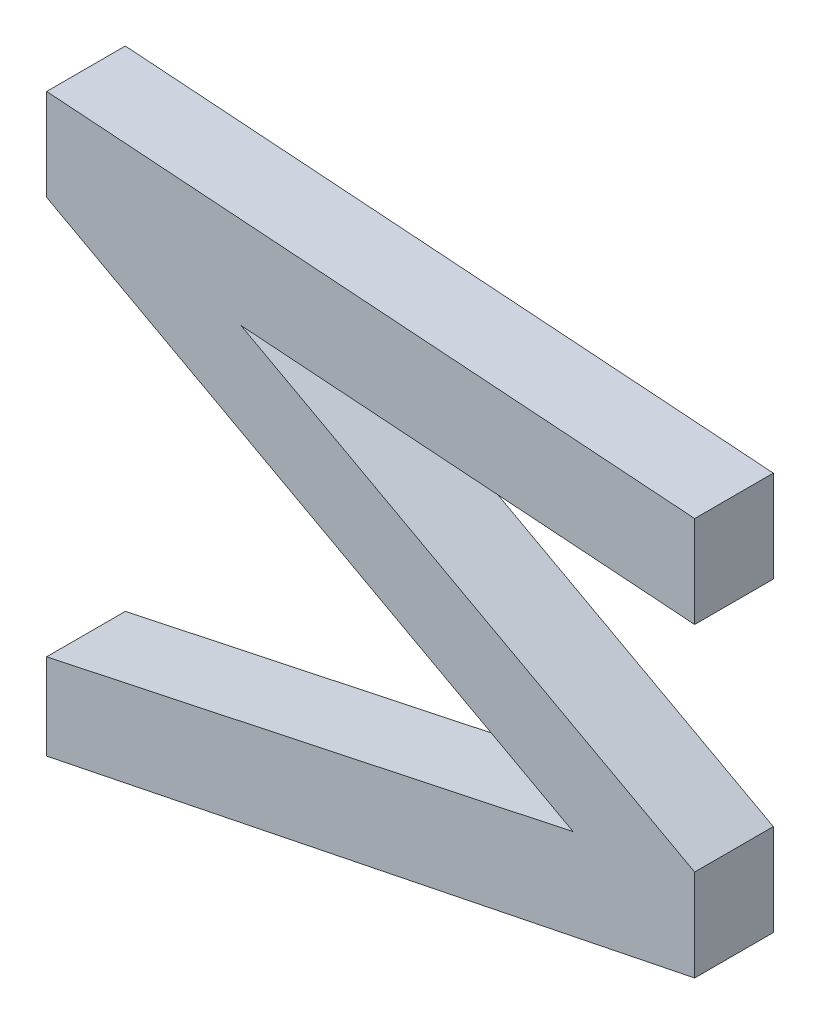
SolidWorks part; units mm, degrees
material "ABS"
ref_plane "Front Plane" through (0, 0, 0) normal (0, 0, 1) x (1, 0, 0)
ref_plane "Top Plane" through (0, 0, 0) normal (0, 1, 0) x (1, 0, 0)
ref_plane "Right Plane" through (0, 0, 0) normal (1, 0, 0) x (0, 0, -1)
sketch "Sketch1" plane through (0, 0, 74.3091) normal (0, 0, 1) x (1, 0, 0)
  line L0 (-16.8386, 48.4772) -> (-79.602, 52.9222)
  line L1 (-79.602, 52.9222) -> (-79.602, 44.0322)
  line L2 (-79.602, 37.7408) -> (-79.602, 52.9222) construction
  line L3 (-16.8386, 48.4772) -> (-16.8386, 39.5872)
  line L4 (-16.8386, 48.4772) -> (-16.8386, 9.9372) construction
  line L5 (-28.6045, 40.4205) -> (-60.7836, 42.6995)
  line L6 (-16.8386, 9.9372) -> (-79.602, -2.8314)
  line L7 (-79.602, -2.8314) -> (-79.602, 5.4998)
  line L8 (-16.8386, 9.9372) -> (-16.8386, 18.8272)
  line L9 (-28.6045, 16.3288) -> (-61.6277, 9.3165)
  line L10 (-28.6045, 40.4205) -> (-16.8386, 39.5872)
  line L11 (-61.6277, 9.3165) -> (-79.602, 5.4998)
  line L12 (-60.7836, 42.6995) -> (-16.8386, 18.8272)
  line L13 (-79.602, 44.0322) -> (-28.6045, 16.3288)
  dimension "D1" = 8.89
  dimension "D2" = 8.89
  dimension "D3" = 8.3312
  dimension "D4" = 8.89
extrude "Boss-Extrude1" add sketch "Sketch1" against normal blind 7.62
